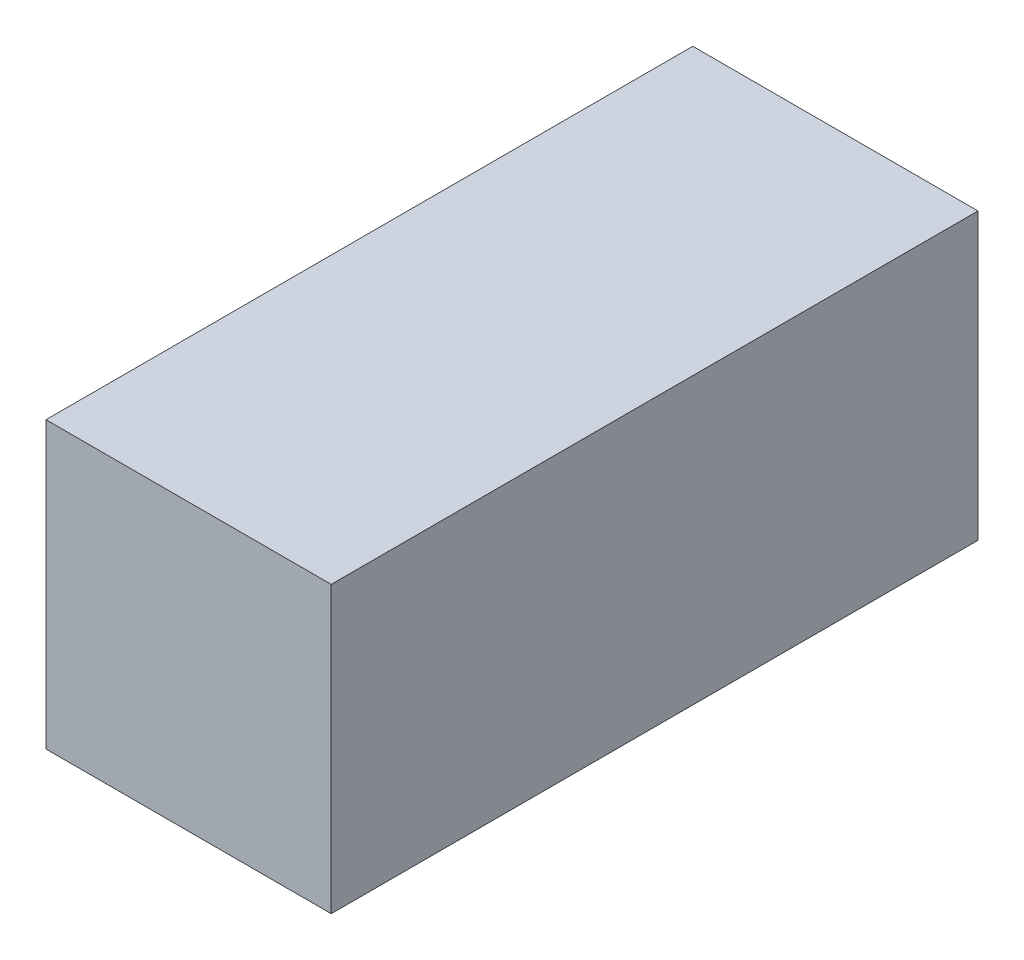
SolidWorks part; units mm, degrees
ref_plane "Front Plane" through (0, 0, 0) normal (0, 0, 1) x (1, 0, 0)
ref_plane "Top Plane" through (0, 0, 0) normal (0, 1, 0) x (1, 0, 0)
ref_plane "Right Plane" through (0, 0, 0) normal (1, 0, 0) x (0, 0, -1)
sketch "Sketch1" plane through (0, 0, 0) normal (0, 1, 0) x (1, 0, 0)
  line L1 (0, 0) -> (-2.69, 0)
  line L2 (0, 0) -> (0, 6.1)
  line L3 (0, 6.1) -> (-2.69, 6.1)
  line L4 (-2.69, 0) -> (-2.69, 6.1)
  dimension "D1" = 2.69
  dimension "D2" = 6.1
extrude "Boss-Extrude1" add sketch "Sketch1" along normal blind 2.69
